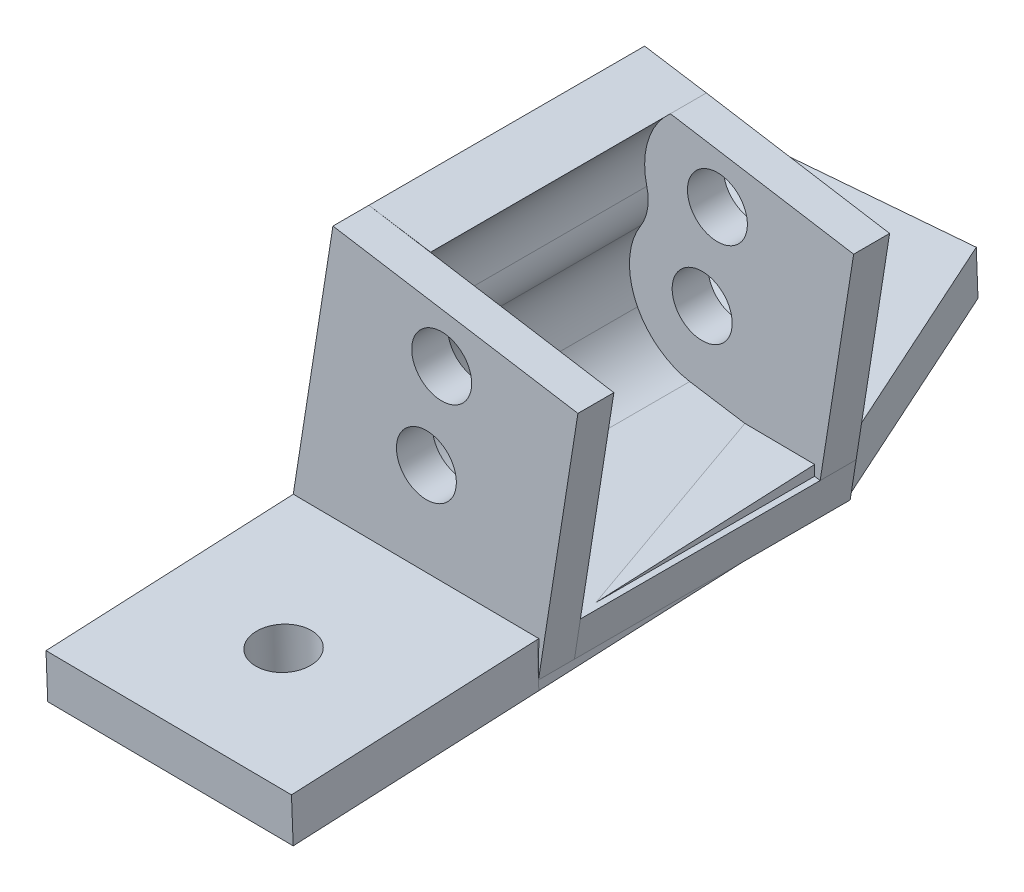
SolidWorks part; units mm, degrees
ref_plane "Front Plane" through (0, 0, 0) normal (0, 0, 1) x (1, 0, 0)
ref_plane "Top Plane" through (0, 0, 0) normal (0, 1, 0) x (1, 0, 0)
ref_plane "Right Plane" through (0, 0, 0) normal (1, 0, 0) x (0, 0, -1)
sketch "Sketch1" plane through (0, 0, 0) normal (0, 0, 1) x (1, 0, 0)
  line L0 (-441.547, 275.0125) -> (-445.7419, 248.3436)
  line L1 (-445.7419, 248.3436) -> (-471.7146, 252.429)
  line L2 (-471.7146, 252.429) -> (-467.5196, 279.0979)
  line L3 (-467.5196, 279.0979) -> (-441.547, 275.0125)
  line L4 (-457.3637, 254.2751) -> (-445.1121, 252.3479)
  line L5 (-457.3637, 254.2751) -> (-458.9271, 254.521)
  arc A0 (-460.9781, 278.069) -> (-463.4772, 270.1621) centre (-455.7189, 272.0583) ccw
  arc A1 (-463.4772, 270.1621) -> (-464.1208, 266.2396) centre (-468.4079, 268.957) cw
  arc A2 (-464.1208, 266.2396) -> (-464.4679, 258.6072) centre (-457.6212, 262.1199) ccw
  arc A3 (-464.4679, 258.6072) -> (-458.9271, 254.521) centre (-457.5873, 262.1373) ccw
  dimension "D1" = 4.064
  dimension "D2" = 6.3254
extrude "Boss-Extrude1" add sketch "Sketch1" against normal blind 29.21 contours A3 A2 A1 A0 L3 L2 L1 L0 L4 L5
sketch "Sketch2" plane through (0, 0, 0) normal (0, 0, 1) x (1, 0, 0)
  line L0 (-467.5196, 279.0979) -> (-471.7146, 252.429)
  line L1 (-471.7146, 252.429) -> (-445.7419, 248.3436)
  line L2 (-467.5196, 279.0979) -> (-441.5658, 274.8877)
  line L3 (-441.5658, 274.8877) -> (-445.7419, 248.3436)
  circle A0 centre (-455.9966, 271.9877) radius 3.175
  circle A1 centre (-457.6159, 262.1197) radius 3.175
extrude "Boss-Extrude2" add sketch "Sketch2" along normal blind 3.81
sketch "Sketch3" plane through (0, 0, -29.21) normal (0, 0, -1) x (-1, 0, 0)
  line L0 (460.9781, 278.069) -> (441.5658, 274.8877)
  line L1 (441.5658, 274.8877) -> (445.1121, 252.3479)
  line L2 (445.1121, 252.3479) -> (458.9271, 254.521)
  arc A0 (458.9271, 254.521) -> (464.1208, 266.2396) centre (457.612, 262.114) ccw
  arc A1 (464.1208, 266.2396) -> (463.4772, 270.1621) centre (468.4079, 268.957) cw
  arc A2 (460.9781, 278.069) -> (463.4772, 270.1621) centre (455.7189, 272.0583) cw
  circle A3 centre (455.9966, 271.9877) radius 3.175
  circle A4 centre (457.612, 262.114) radius 3.1818
extrude "Boss-Extrude3" add sketch "Sketch3" against normal up to surface (3.81 mm away)
ref_plane "Plane2" through (2.2797, 246.1135, 11.6073) normal (0.0093, 0.9988, 0.0471) x (1, -0.0092, -0.0004)
sketch "Sketch4" plane through (2.2797, 246.1135, 11.6073) normal (0.0093, 0.9988, 0.0471) x (1, -0.0092, -0.0004)
  line L0 (-448.0196, 7.8937) -> (-448.0196, -18.1592)
  line L1 (-448.0196, -18.1592) -> (-474.0145, -18.1592)
  line L2 (-474.0145, -18.1592) -> (-474.0289, 8.0862)
  line L3 (-448.0052, 40.8771) -> (-458.003, 64.4655)
  line L4 (-450.9953, 32.2464) -> (-508.2264, 295.3771) construction
  line L5 (-474.0145, 41.0695) -> (-483.5335, 62.1016)
  line L6 (-483.5335, 62.1016) -> (-458.003, 64.4655)
  line L7 (-448.0052, 40.8771) -> (-448.0196, 7.8937)
  line L8 (-474.0145, 41.0695) -> (-474.0289, 8.0862)
  circle A0 centre (-465.8636, 52.1133) radius 3.1097
  circle A1 centre (-461.1806, -5.8176) radius 2.9774
extrude "Boss-Extrude4" add sketch "Sketch4" against normal blind 3.302 and the other way blind 1.524
